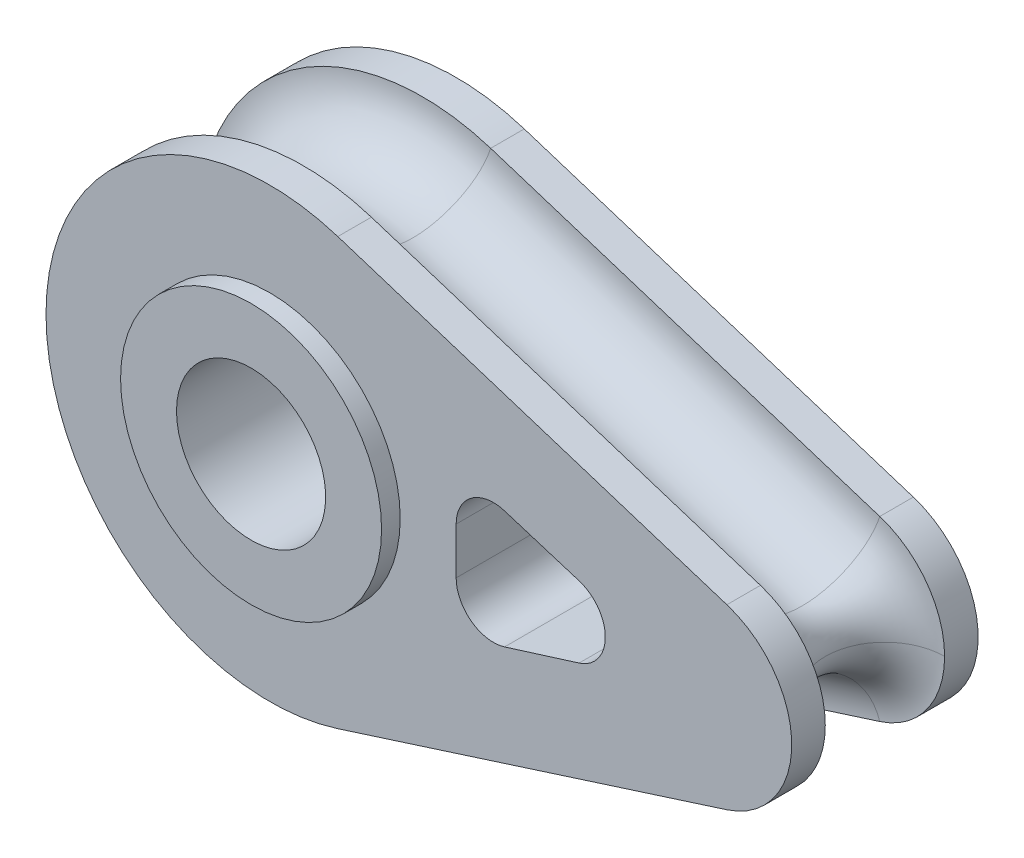
SolidWorks part; units mm, degrees
ref_plane "前视基准面" through (0, 0, 0) normal (0, 0, 1) x (1, 0, 0)
ref_plane "上视基准面" through (0, 0, 0) normal (0, 1, 0) x (1, 0, 0)
ref_plane "右视基准面" through (0, 0, 0) normal (1, 0, 0) x (0, 0, -1)
sketch "草图1" plane through (0, 0, 0) normal (0, 0, 1) x (1, 0, 0)
  line L0 (18.2609, 57.1537) -> (122.6087, 23.814)
  line L1 (18.2609, -57.1537) -> (122.6087, -23.814)
  line L2 (50, -6.25) -> (50, 6.25)
  line L3 (62.9827, 15.7948) -> (82.9827, 9.5448)
  line L4 (62.9827, -15.7948) -> (82.9827, -9.5448)
  line L5 (115, 0) -> (80, 0) construction
  arc A0 (18.2609, 57.1537) -> (18.2609, -57.1537) centre (0, 0) ccw
  arc A1 (122.6087, -23.814) -> (122.6087, 23.814) centre (115, 0) ccw
  arc A2 (62.9827, 15.7948) -> (50, 6.25) centre (60, 6.25) ccw
  arc A3 (82.9827, -9.5448) -> (82.9827, 9.5448) centre (80, 0) ccw
  arc A4 (50, -6.25) -> (62.9827, -15.7948) centre (60, -6.25) ccw
  circle A5 centre (0, 0) radius 20
  dimension "D1" = 120
  dimension "D2" = 50
  dimension "D4" = 20
  dimension "D5" = 20
  dimension "D6" = 20
  dimension "D10" = 40
  dimension "D3" = 115
  dimension "D7" = 35
  dimension "D8" = 55
  dimension "D9" = 12.5
extrude "凸台-拉伸1" add sketch "草图1" along normal blind 50
sketch "草图2" plane through (0, 0, 0) normal (0, 0, -1) x (-1, 0, 0)
  circle A0 centre (0, 0) radius 20
  circle A1 centre (0, 0) radius 35
  dimension "D1" = 40
  dimension "D2" = 70
extrude "凸台-拉伸2" add sketch "草图2" along normal blind 5
ref_plane "基准面4" through (0, 0, 25) normal (0, 0, -1) x (-1, 0, 0)
mirror "镜向1" about plane through (0, 0, 25) normal (0, 0, -1) of "凸台-拉伸2"
ref_plane "基准面5" through (0, 0, 0) normal (0, -1, 0) x (-1, 0, 0)
sketch "草图3" plane through (0, 0, 0) normal (0, -1, 0) x (-1, 0, 0)
  line L2 (-122.6087, 0) -> (-140, 0) construction
  line L3 (-140, -58.1007) -> (-140, 8.1007) construction
  circle A1 centre (-140, -25) radius 16
  dimension "D1" = 32
  dimension "D2" = 25
  dimension "D3" = 140
sketch "草图6" plane through (0, 0, 25) normal (0, 0, -1) x (-1, 0, 0)
  line L0 (-122.6087, 23.814) -> (-18.2609, 57.1537)
  line L1 (-122.6087, -23.814) -> (-18.2609, -57.1537)
  arc A0 (-18.2609, -57.1537) -> (-18.2609, 57.1537) centre (0, 0) ccw
  arc A1 (-122.6087, 23.814) -> (-122.6087, -23.814) centre (-115, 0) ccw
  arc A2 (-18.2609, -57.1537) -> (-18.2609, 57.1537) centre (0, 0) ccw construction
  arc A3 (-122.6087, 23.814) -> (-122.6087, -23.814) centre (-115, 0) ccw construction
  point P14 (-168.1988, 9.2478)
sweep "切除-扫描1" cut profiles "草图3" path "草图6"
